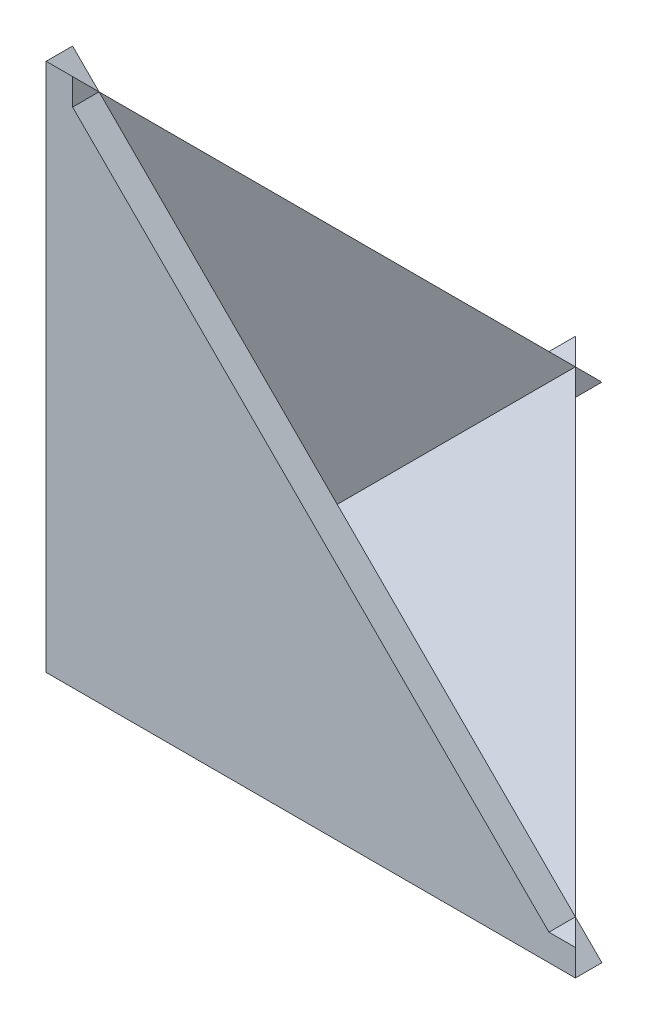
SolidWorks part; units mm, degrees
ref_plane "Front Plane" through (0, 0, 0) normal (0, 0, 1) x (1, 0, 0)
ref_plane "Top Plane" through (0, 0, 0) normal (0, 1, 0) x (1, 0, 0)
ref_plane "Right Plane" through (0, 0, 0) normal (1, 0, 0) x (0, 0, -1)
sketch "Sketch2" plane through (0, 0, 0) normal (0, 1, 0) x (1, 0, 0)
  line L0 (0, 10) -> (0, 0)
  line L1 (0, 0) -> (10, 0)
  line L2 (10, 0) -> (0, 10)
  dimension "D1" = 10
extrude "Boss-Extrude5" add sketch "Sketch2" along normal blind 0.5
sketch "Sketch3" plane through (0, 0, 0) normal (0, 0, 1) x (1, 0, 0)
  line L0 (0, 0) -> (0, 10)
  line L1 (0, 10) -> (10, 0)
  line L2 (0, 0) -> (10, 0) construction
  line L3 (0, 0) -> (10, 0)
extrude "Boss-Extrude6" add sketch "Sketch3" against normal blind 0.5
sketch "Sketch4" plane through (0, 0, 0) normal (-1, 0, 0) x (0, 0, 1)
  line L0 (-10, 0) -> (0, 0)
  line L1 (0, 0) -> (0, 10)
  line L2 (0, 10) -> (-10, 0)
extrude "Boss-Extrude7" add sketch "Sketch4" against normal blind 0.5
